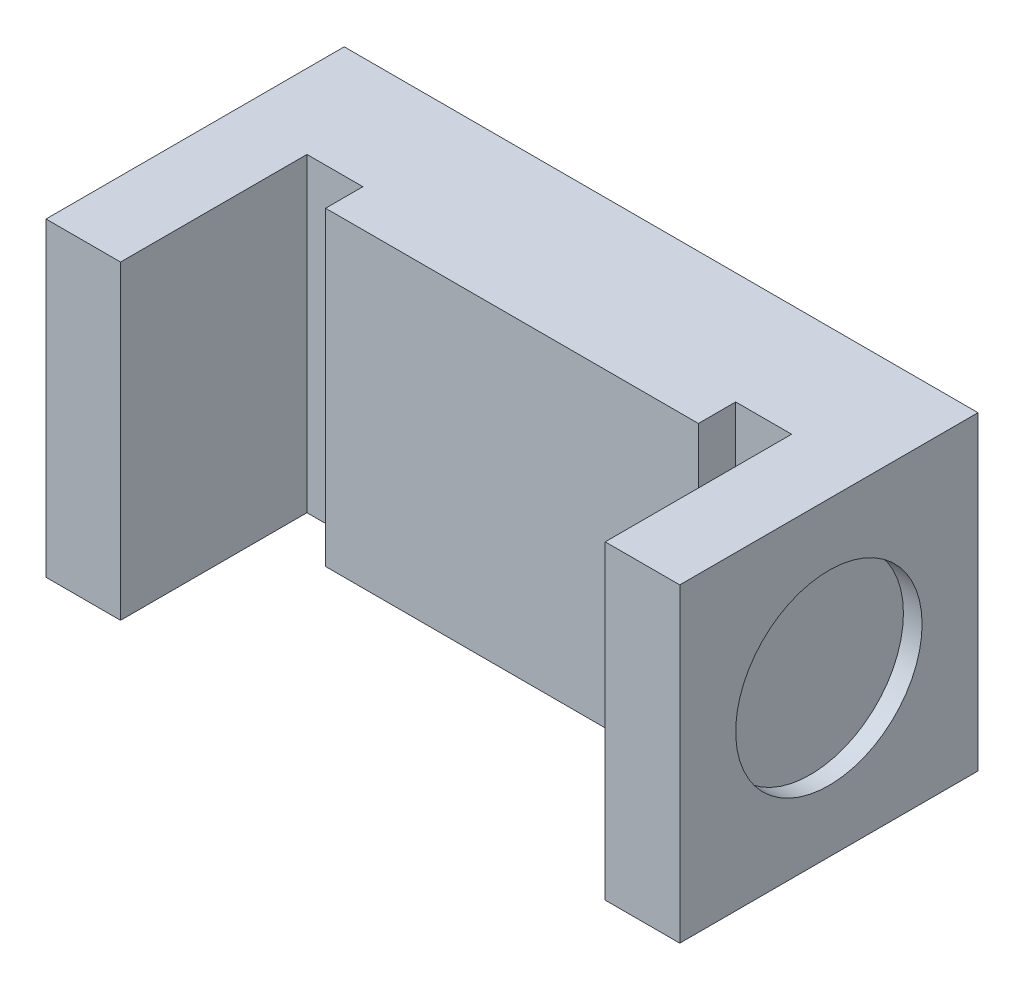
SolidWorks part; units mm, degrees
ref_plane "Front Plane" through (0, 0, 0) normal (0, 0, 1) x (1, 0, 0)
ref_plane "Top Plane" through (0, 0, 0) normal (0, 1, 0) x (1, 0, 0)
ref_plane "Right Plane" through (0, 0, 0) normal (1, 0, 0) x (0, 0, -1)
sketch "Sketch1" plane through (0, 0, 0) normal (0, 0, 1) x (1, 0, 0)
  line L1 (-65, 41.6192) -> (65, 41.6192)
  line L2 (-65, 41.6192) -> (-65, -41.6192)
  line L3 (-65, -41.6192) -> (65, -41.6192)
  line L4 (65, 41.6192) -> (65, -41.6192)
  line L5 (-65, 41.6192) -> (65, -41.6192) construction
  line L6 (-65, -41.6192) -> (65, 41.6192) construction
  point P0 (0, 0)
  dimension "D1" = 130
extrude "Boss-Extrude1" add sketch "Sketch1" along normal blind 30
sketch "Sketch2" plane through (0, 0, 30) normal (0, 0, 1) x (1, 0, 0)
  line L0 (-65, -41.6192) -> (65, -41.6192) construction
  line L1 (-50, 41.6192) -> (50, 41.6192)
  line L2 (-50, 41.6192) -> (-50, -41.6192)
  line L3 (-50, -41.6192) -> (50, -41.6192)
  line L4 (50, 41.6192) -> (50, -41.6192)
  line L5 (-50, 41.6192) -> (50, -41.6192) construction
  line L6 (-50, -41.6192) -> (50, 41.6192) construction
  point P0 (0, 0)
  dimension "D1" = 100
extrude "Boss-Extrude2" add sketch "Sketch2" along normal blind 10
sketch "Sketch3" plane through (-65, 0, 0) normal (-1, 0, 0) x (0, 0, 1)
  line L1 (0, 41.6192) -> (80, 41.6192)
  line L2 (0, 41.6192) -> (0, -41.6192)
  line L3 (0, -41.6192) -> (80, -41.6192)
  line L4 (80, 41.6192) -> (80, -41.6192)
  dimension "D1" = 80
extrude "Boss-Extrude3" add sketch "Sketch3" along normal blind 20
sketch "Sketch4" plane through (-85, 0, 0) normal (-1, 0, 0) x (0, 0, 1)
  line L0 (0, 41.6192) -> (80, -41.6192) construction
  circle A0 centre (40, 0) radius 25
  dimension "D1" = 50
extrude "Cut-Extrude1" cut sketch "Sketch4" against normal blind 5
sketch "Sketch5" plane through (65, 0, 0) normal (1, 0, 0) x (0, 0, -1)
  line L0 (-30, -41.6192) -> (-80, -41.6192) construction
  line L1 (0, 41.6192) -> (-80, 41.6192)
  line L2 (0, 41.6192) -> (0, -41.6192)
  line L3 (0, -41.6192) -> (-80, -41.6192)
  line L4 (-80, 41.6192) -> (-80, -41.6192)
  dimension "D1" = 80
extrude "Boss-Extrude4" add sketch "Sketch5" along normal blind 20
sketch "Sketch6" plane through (85, 0, 0) normal (1, 0, 0) x (0, 0, -1)
  line L0 (-80, 41.6192) -> (0, -41.6192) construction
  circle A0 centre (-40, 0) radius 25
  dimension "D1" = 50
extrude "Cut-Extrude2" cut sketch "Sketch6" against normal blind 5
sketch "Sketch7" plane through (0, 0, 0) normal (0, 0, -1) x (-1, 0, 0)
  line L0 (85, -41.6192) -> (-85, -41.6192) construction
  line L1 (-40, -31.6192) -> (40, -31.6192)
  line L2 (-40, -31.6192) -> (-40, -51.6192)
  line L3 (-40, -51.6192) -> (40, -51.6192)
  line L4 (40, -31.6192) -> (40, -51.6192)
  line L5 (-40, -31.6192) -> (40, -51.6192) construction
  line L6 (-40, -51.6192) -> (40, -31.6192) construction
  point P0 (0, -41.6192)
  dimension "D1" = 80
  dimension "D2" = 20
extrude "Boss-Extrude5" add sketch "Sketch7" along normal blind 5
sketch "Sketch8" plane through (0, 0, 0) normal (0, 0, -1) x (-1, 0, 0)
  line L1 (-42.5, 25) -> (42.5, 25)
  line L2 (-42.5, 25) -> (-42.5, -25)
  line L3 (-42.5, -25) -> (42.5, -25)
  line L4 (42.5, 25) -> (42.5, -25)
  line L5 (-42.5, 25) -> (42.5, -25) construction
  line L6 (-42.5, -25) -> (42.5, 25) construction
  point P0 (0, 0)
  dimension "D1" = 50
  dimension "D2" = 85
extrude "Boss-Extrude6" add sketch "Sketch8" along normal blind 30
sketch "Sketch9" plane through (0, 0, -30) normal (0, 0, -1) x (-1, 0, 0)
  line L0 (42.5, -25) -> (42.5, 25) construction
  line L1 (-42.5, 25) -> (42.5, 25)
  line L2 (-42.5, 25) -> (-42.5, 0)
  line L3 (-42.5, 0) -> (42.5, 0)
  line L4 (42.5, 25) -> (42.5, 0)
extrude "Cut-Extrude3" cut sketch "Sketch9" against normal blind 15
sketch "Sketch10" plane through (0, 0, 0) normal (0, 1, 0) x (1, 0, 0)
  line L0 (-42.5, 15) -> (42.5, 15) construction
  line L1 (-42.5, 30) -> (-12.5, 30)
  line L2 (-42.5, 30) -> (-42.5, 15)
  line L3 (-42.5, 15) -> (-12.5, 15)
  line L4 (-12.5, 30) -> (-12.5, 15)
  line L5 (42.5, 15) -> (-42.5, 15) construction
  line L6 (42.5, 30) -> (12.5, 30)
  line L7 (42.5, 30) -> (42.5, 15)
  line L8 (42.5, 15) -> (12.5, 15)
  line L9 (12.5, 30) -> (12.5, 15)
  dimension "D1" = 30
extrude "Cut-Extrude4" cut sketch "Sketch10" against normal through all
